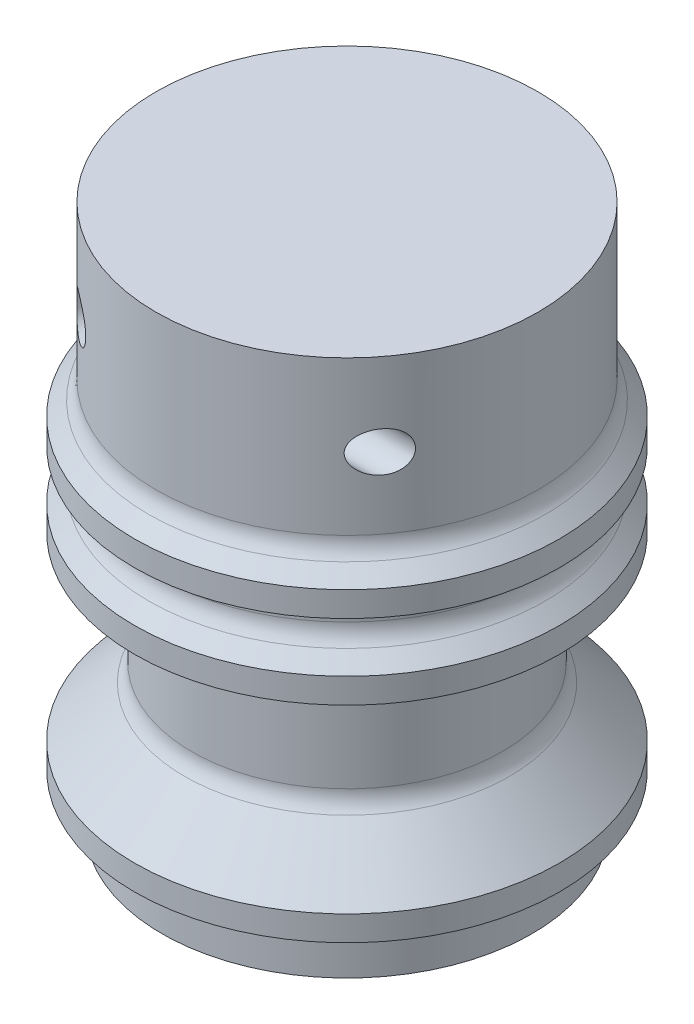
SolidWorks part; units mm, degrees
ref_plane "Plano frontal" through (0, 0, 0) normal (0, 0, 1) x (1, 0, 0)
ref_plane "Plano superior" through (0, 0, 0) normal (0, 1, 0) x (1, 0, 0)
ref_plane "Plano direito" through (0, 0, 0) normal (1, 0, 0) x (0, 0, -1)
sketch "Cut_1" plane through (0, 0, 0) normal (0, 1, 0) x (1, 0, 0)
  line L0 (4.658, 6.0576) -> (4.658, 2.8486) construction
  line L1 (3.856, 3.8656) -> (3.856, 6.5972)
  line L2 (5.46, 0) -> (5.46, 5.346)
  line L3 (3.856, 3.8656) -> (4.658, 3.8656) construction
  line L4 (4.658, 3.8656) -> (5.46, 3.8656) construction
  circle A0 centre (0, 0) radius 5.46
  circle A2 centre (0, 0) radius 7.6414
  circle A4 centre (0, 0) radius 3.105
  dimension "D1" = 10.92
  dimension "D5" = 15.2829
  dimension "D6" = 6.21
  dimension "D2" = 4.658
  dimension "D3" = 1.604
  dimension "D4" = 3.209
  dimension "D7" = 0.802
sketch "Cut_2" plane through (0, 0, 0) normal (0, 1, 0) x (1, 0, 0)
  line L0 (4.889, 0) -> (4.889, 3.8203)
  line L1 (3.797, 3.0798) -> (3.797, 4.9071)
  line L2 (3.797, 3.0798) -> (4.343, 3.0798) construction
  line L3 (4.343, 3.0798) -> (4.889, 3.0798) construction
  line L4 (4.343, 4.4311) -> (4.343, 2.2451) construction
  circle A0 centre (0, 0) radius 4.889
  circle A1 centre (0, 0) radius 6.2046
  circle A2 centre (0, 0) radius 4.889
  circle A3 centre (0, 0) radius 5.798
  dimension "D1" = 9.778
  dimension "D2" = 4.343
  dimension "D5" = 12.4091
  dimension "D6" = 9.778
  dimension "D7" = 11.596
  dimension "D3" = 1.092
  dimension "D4" = 2.186
  dimension "D8" = 0.546
sketch "Esboço4" plane through (0, 0, 0) normal (0, 0, 1) x (1, 0, 0)
  line L0 (0, 0) -> (0, 9.8449) construction
  line L1 (4.889, 0) -> (4.889, 4.889) construction
  line L2 (3.105, 1) -> (3.105, 10.329)
  line L3 (3.105, 10.329) -> (5.46, 12.684)
  line L4 (5.46, 12.684) -> (5.46, 19.658)
  line L5 (5.46, 19.658) -> (0, 19.658)
  line L6 (0, 19.658) -> (0, 21.658)
  line L7 (0, 21.658) -> (7.6414, 21.658)
  line L8 (7.6414, 21.658) -> (7.6414, 10.732)
  line L9 (7.6414, 10.732) -> (6.2046, 10.732)
  line L10 (6.2046, 10.732) -> (6.2046, 4)
  line L11 (6.2046, 4) -> (7.4, 4)
  line L12 (7.4, 4) -> (7.4, 0)
  line L13 (7.4, 0) -> (5.798, 0)
  line L14 (4.889, 4.4734) -> (4.889, 4.889)
  line L16 (4.889, 4.889) -> (4.889, 9.232)
  line L17 (4.889, 9.232) -> (4.105, 9.232)
  line L18 (4.105, 9.232) -> (4.105, 1)
  line L19 (4.105, 1) -> (3.105, 1)
  line L21 (6.2046, 4) -> (6.2046, 0) construction
  line L22 (5.798, 0) -> (5.798, 2.899)
  line L23 (4.889, 0) -> (-4.889, 0) construction
  line L24 (5.798, 2.899) -> (4.889, 4.4734)
  line L25 (5.46, 12.684) -> (5.46, 0) construction
  line L26 (3.105, 1) -> (3.105, 0) construction
  line L28 (7.6414, 10.732) -> (7.6414, 0) construction
  line L29 (4.889, 4.4734) -> (4.889, 0) construction
  line L32 (0, 9.232) -> (4.28, 9.232) construction
  dimension "D1" = 1
  dimension "D2" = 14.8
  dimension "D3" = 1
  dimension "D4" = 4
  dimension "D5" = 45
  dimension "D6" = 9.329
  dimension "D7" = 4.343
  dimension "D8" = 2
  dimension "D9" = 30
  dimension "D10" = 9.329
  dimension "D11" = 1.5
  dimension "D12" = 4.889
  dimension "D13" = 1.1954
  dimension "D14" = 4.28
  dimension "D16" = 2.899
revolve "Revolução1" add sketch "Esboço4" angle 360 about L0
sketch "Esboço5" plane through (0, 0, 0) normal (0, 0, 1) x (1, 0, 0)
  line L0 (0, 0) -> (0, 18.356) construction
  line L1 (4.889, 0) -> (-4.889, 0) construction
  line L2 (0, 18.356) -> (0, 19.658) construction
  line L3 (0, 18.356) -> (4.658, 18.356) construction
  line L4 (4.658, 18.356) -> (4.658, 0) construction
  line L5 (-5.46, 19.658) -> (5.46, 19.658) construction
  line L6 (-4.105, 0) -> (-4.105, 8.186) construction
  line L7 (5.46, 0) -> (-5.46, 0) construction
  line L8 (-4.105, 8.186) -> (-4.105, 9.232) construction
  line L9 (-4.105, 8.186) -> (-4.343, 8.186) construction
  line L10 (-4.343, 8.186) -> (-4.343, 0) construction
  line L15 (-4.343, 0) -> (0, 0) construction
  line L16 (0, 0) -> (4.343, 0) construction
  line L17 (4.889, 0) -> (-4.889, 0) construction
  circle A0 centre (4.658, 18.356) radius 0.802
  circle A1 centre (-4.343, 8.186) radius 0.546
  dimension "D1" = 1.604
  dimension "D3" = 1.092
  dimension "D2" = 1.302
  dimension "D4" = 1.046
extrude "Inlet_1" cut sketch "Esboço5" against normal through all contours A0
pattern_circular "PadrãoCircular1" count 4 over 360 about axis through (0, 0, 0) along (0, -1, 0) of "Inlet_1"
ref_plane "Plano1" through (0, 0, -10) normal (0, 0, 1) x (1, 0, 0)
sketch "Esboço9" plane through (0, 0, -10) normal (0, 0, 1) x (1, 0, 0)
  circle A0 centre (-4.343, 8.186) radius 0.546
  circle A1 centre (-4.343, 8.186) radius 0.546 construction
extrude "Corte-extrusão1" [suppressed] cut sketch "Esboço9" along normal up to surface (6.9202 mm away) contours A0
pattern_circular "PadrãoCircular2" [suppressed] count 4 over 360
chamfer "Chanfro1" [suppressed] distance 1 angle 45
fillet "Filete3" [suppressed] radius 1
fillet "Filete_topo" radius 0.35 3 edges at (0, 9.232, -4.889) (0, 19.658, -5.46) (0, 9.232, -4.105)
fillet "Filete_base" radius 2 4 edges at (0, 10.329, -3.105) (0, 12.684, -5.46) (0, 2.899, -5.798) (0, 4.4734, -4.889)
sketch "Esboço11" plane through (0, 0, 0) normal (0, 0, 1) x (1, 0, 0)
  line L0 (6.2046, 10.232) -> (8.5, 10.232)
  line L1 (8.5, 10.232) -> (8.5, 11.232)
  line L2 (8.5, 11.232) -> (7.6414, 12.0906)
  line L3 (7.6414, 12.0906) -> (7.6414, 13.232)
  line L4 (7.6414, 13.232) -> (8.5, 13.232)
  line L5 (8.5, 13.232) -> (8.5, 14.232)
  line L6 (8.5, 14.232) -> (7.6414, 15.0906)
  line L7 (7.6414, 15.0906) -> (7.1414, 15.0906)
  line L8 (7.1414, 15.0906) -> (7.1414, 11.232)
  line L9 (7.1414, 11.232) -> (5.7046, 11.232)
  line L10 (5.7046, 11.232) -> (5.7046, 10.232)
  line L11 (5.7046, 10.232) -> (6.2046, 10.232)
  line L12 (7.4, 2) -> (8.5, 2)
  line L13 (8.5, 2) -> (8.5, 3)
  line L14 (8.5, 3) -> (6.2046, 5.2954)
  line L15 (6.2046, 5.2954) -> (5.7046, 5.2954)
  line L16 (5.7046, 5.2954) -> (5.7046, 4)
  line L17 (5.7046, 4) -> (6.9, 2)
  line L18 (6.9, 2) -> (7.4, 2)
  line L19 (7.6414, 15.0906) -> (7.6414, 10.732) construction
  line L20 (5.7046, 4) -> (6.2046, 4) construction
  line L22 (6.2046, 10.232) -> (6.2046, 10.732) construction
  line L23 (6.2046, 10.732) -> (6.2046, 11.232) construction
  line L26 (0, 0) -> (0, 7.0334) construction
  line L27 (7.4, 2) -> (7.4, 0) construction
  line L30 (6.2046, 5.2954) -> (6.2046, 4) construction
  dimension "D1" = 0.5
  dimension "D2" = 0.5
  dimension "D3" = 1
  dimension "D4" = 4
  dimension "D5" = 45
  dimension "D6" = 0.5
  dimension "D7" = 0.5
  dimension "D8" = 17
  dimension "D9" = 0.5
  dimension "D10" = 2
  dimension "D11" = 0.5
  dimension "D12" = 45
  dimension "D13" = 1
  dimension "D15" = 0.8586
  dimension "D16" = 1.1414
revolve "Revolução2" add sketch "Esboço11" angle 360 about L26
fillet "Filete4" radius 1 4 edges at (0, 12.0906, -7.6414) (0, 15.0906, 7.6414) (0, 5.2954, 6.2046) (0, 10.232, -6.2046)
fillet "Filete5" radius 0.5 2 edges at (0, 2, -7.4) (0, 13.232, -7.6414)
sketch "Esboço12" plane through (0, 0, 0) normal (0, 0, 1) x (1, 0, 0)
  line L6 (0, 0) -> (0, -2.4571) construction
  line L8 (-3.6459, 1) -> (-6.4914, 1)
  line L9 (-6.4914, 1) -> (-6.4914, 3.6584)
  line L10 (-6.4914, 3.6584) -> (-5.3962, 5.8113)
  line L11 (-5.3962, 5.8113) -> (-5.3962, 9.8877)
  line L12 (-5.3962, 9.8877) -> (-3.6459, 9.8877)
  line L13 (-3.6459, 9.8877) -> (-3.6459, 1)
  line L14 (-4.105, 1) -> (4.105, 1) construction
  point P11 (0, 0)
  point P12 (-5.3962, 9.8877)
  point P13 (-6.4914, 3.6584)
  dimension "D1" = 7.2919
  dimension "D2" = 12.9827
  dimension "D3" = 8.8877
  dimension "D4" = 26.961
  dimension "D5" = 10.7925
  dimension "D6" = 2.6584
revolve "Revolução3" add sketch "Esboço12" angle 360 about L6
equation "\"D2@Esboço5\"=\"D1@Esboço5\"/2+0.5"
equation "\"D4@Esboço5\"=\"D3@Esboço5\"/2+0.5"
